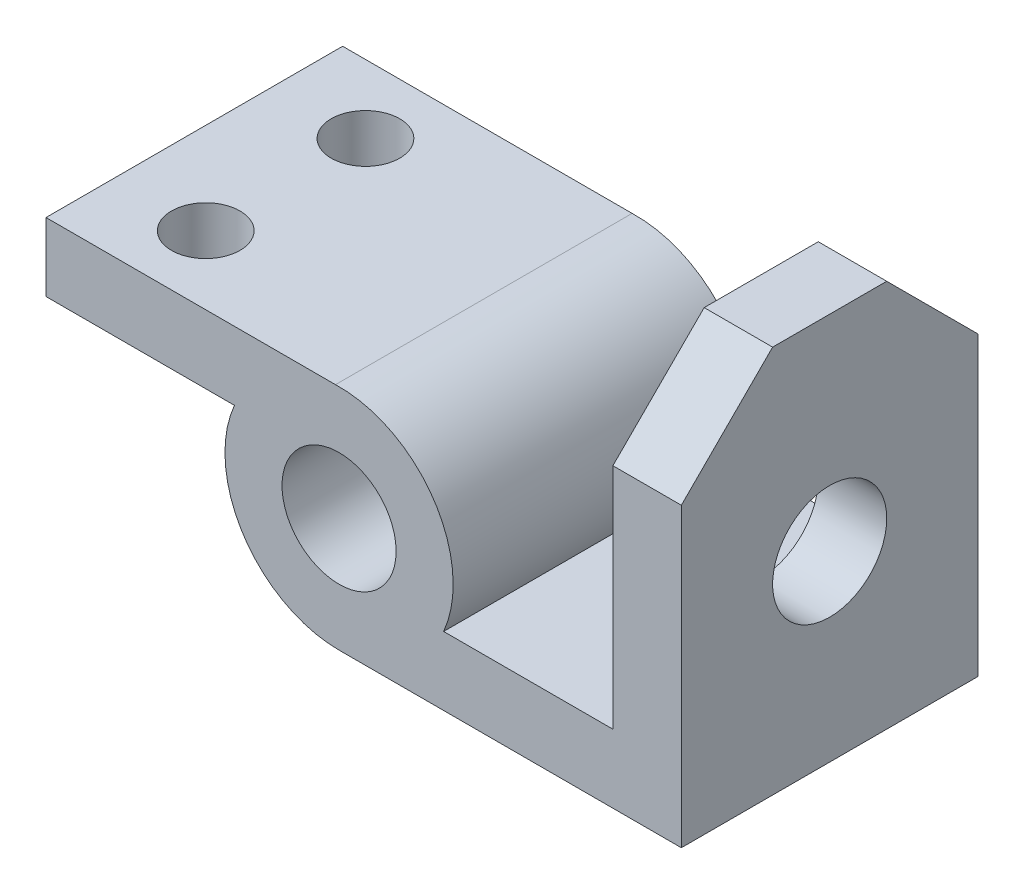
SolidWorks part; units mm, degrees
ref_plane "Front Plane" through (0, 0, 0) normal (0, 0, 1) x (1, 0, 0)
ref_plane "Top Plane" through (0, 0, 0) normal (0, 1, 0) x (1, 0, 0)
ref_plane "Right Plane" through (0, 0, 0) normal (1, 0, 0) x (0, 0, -1)
sketch "Sketch1" plane through (0, 0, 0) normal (0, 0, 1) x (1, 0, 0)
  circle A0 centre (0, 0) radius 15.875
  circle A1 centre (0, 0) radius 31.75
  dimension "D1" = 31.75
  dimension "D2" = 63.5
extrude "Boss-Extrude1" add sketch "Sketch1" against normal blind 82.55
sketch "Sketch3" plane through (0, 0, 0) normal (0, 0, 1) x (1, 0, 0)
  line L1 (0.9971, 31.7343) -> (-81.5529, 31.7343)
  line L3 (-29.1062, 12.6843) -> (-81.5529, 12.6843)
  line L4 (-81.5529, 31.7343) -> (-81.5529, 12.6843)
  line L5 (0, -31.75) -> (95.25, -31.75)
  line L6 (95.25, -31.75) -> (95.25, -12.7)
  line L7 (95.25, -12.7) -> (29.0994, -12.7)
  line L8 (0.9971, 31.7343) -> (-29.1062, 12.6843)
  line L9 (0, -31.75) -> (29.0994, -12.7)
  circle A0 centre (0, 0) radius 31.75 construction
  dimension "D1" = 19.05
  dimension "D2" = 82.55
  dimension "D3" = 19.05
  dimension "D4" = 95.25
  dimension "D5" = 66.1506
  dimension "D6" = 52.4467
extrude "Boss-Extrude2" add sketch "Sketch3" against normal blind 82.55
sketch "Sketch4" plane through (0, 31.7343, 0) normal (0, 1, 0) x (1, 0, 0)
  line L0 (-0.9971, 82.55) -> (-81.5529, 82.55) construction
  line L1 (-81.5529, 82.55) -> (-81.5529, 0) construction
  line L2 (-0.9971, 0) -> (-81.5529, 0) construction
  circle A0 centre (-56.1529, 63.5) radius 9.525
  circle A1 centre (-56.1529, 19.05) radius 9.525
  dimension "D1" = 19.05
  dimension "D2" = 19.05
  dimension "D3" = 19.05
  dimension "D4" = 25.4
  dimension "D5" = 19.05
  dimension "D6" = 25.4
extrude "Cut-Extrude1" cut sketch "Sketch4" against normal blind 82.55
sketch "Sketch5" plane through (0, -12.7, 0) normal (0, 1, 0) x (1, 0, 0)
  line L0 (95.25, 0) -> (29.0994, 0) construction
  line L1 (95.25, 82.55) -> (76.2, 82.55)
  line L2 (95.25, 82.55) -> (95.25, 0)
  line L3 (95.25, 0) -> (76.2, 0)
  line L4 (76.2, 82.55) -> (76.2, 0)
  dimension "D1" = 82.55
  dimension "D2" = 19.05
extrude "Boss-Extrude3" add sketch "Sketch5" along normal blind 88.9
chamfer "Chamfer1" distance 25.4 2 edges at (85.725, 76.2, -82.55) (85.725, 76.2, 0)
sketch "Sketch6" plane through (95.25, 0, 0) normal (1, 0, 0) x (0, 0, -1)
  line L1 (82.55, -31.75) -> (0, -31.75) construction
  line L2 (41.275, -31.75) -> (41.275, 19.05) construction
  circle A0 centre (41.275, 19.05) radius 15.875
  dimension "D1" = 31.75
  dimension "D2" = 50.8
  dimension "D3" = 41.275
extrude "Cut-Extrude2" cut sketch "Sketch6" against normal up to next
